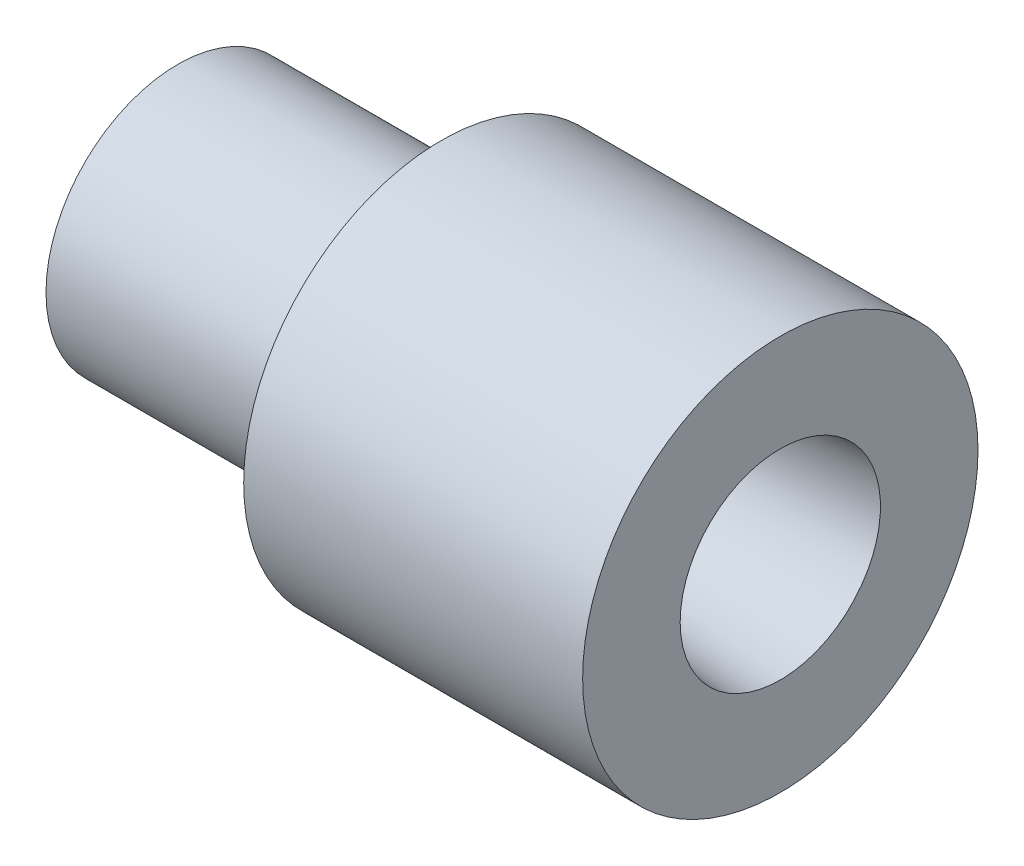
SolidWorks part; units mm, degrees
ref_plane "Front Plane" through (0, 0, 0) normal (0, 0, 1) x (1, 0, 0)
ref_plane "Top Plane" through (0, 0, 0) normal (0, 1, 0) x (1, 0, 0)
ref_plane "Right Plane" through (0, 0, 0) normal (1, 0, 0) x (0, 0, -1)
sketch "Sketch1" plane through (0, 0, 0) normal (0, 1, 0) x (1, 0, 0)
  line L0 (0, 0) -> (0, 2.286) construction
  line L1 (0, 2.286) -> (0, 6.35)
  line L2 (12.7, 9.525) -> (29.0323, 9.525)
  line L3 (29.0323, 9.525) -> (29.0323, 4.826)
  line L4 (29.0323, 4.826) -> (0, 2.286)
  line L5 (0, 0) -> (29.0323, 0) construction
  line L6 (29.0323, 0) -> (29.0323, 4.826) construction
  line L8 (12.7, 6.35) -> (12.7, 9.525)
  line L12 (0, 6.35) -> (12.7, 6.35)
  dimension "D1" = 2.286
  dimension "D2" = 4.826
  dimension "D3" = 5
  dimension "D4" = 9.525
  dimension "D5" = 6.35
  dimension "D6" = 12.7
revolve "Revolve1" add sketch "Sketch1" angle 360 about L5
equation "\"z\" = 8\t\t\t\t'number of blades"
equation "\"de\" = 0.43in\t\t\t'entrance eye diameter"
equation "\"de_length\" = 10mm\t\t'entrance eye consistent length"
equation "\"d_exit\" = 0.18in \t\t'throat aka d1"
equation "\"d2\" = 2.1in \t\t\t'outer diameter of the impeller"
equation "\"b2\" = .2in\t\t\t'tip height from disc surface at d2; slightly higher than d_exit"
equation "\"b1\" = \"b2\" + (\"d2\"/2 - \"de\"/2)*tan(\"theta\") \t\t\t'tip height from disc surface at inlet eye"
equation "\"theta\" = 12\t\t\t'angle of blades from inner to outer "
equation "\"ae\" = 3.14*(\"de\"^2)/4\t\t'entrance eye area'"
equation "\"ce\" = 3.14*\"de\"\t\t'entrance eye circumference"
equation "\"av_ratio\" = .325\t\t'ratio of av/ae at N_s of 470, range is .275 to .375, .325 ideal. High ratio means bigger area means smaller blades"
equation "\"av\" = \"ae\"*\"av_ratio\"\t\t'area between just two blades"
equation "\"s_open\" = \"av\"/\"b1\"\t\t'width of open area"
equation "\"s\"=\"ce\" - \"z\"*\"s_open\""
equation "\"min blade thickness\" = .15in"
equation "\"bearing OD\" = 30mm"
equation "\"bearing ID\"= 10mm"
equation "\"bearing depth\"= 9mm"
equation "\"bearing outer race thickness\"= 1mm"
equation "\"bearing inner race thickness\"= 1mm"
equation "\"bearing bore\" = \"bearing depth\" + 1mm"
equation "\"lower seal OD\" = .917in\t\t'this is https://www.mcmaster.com/#9281k121/=174001b"
equation "\"lower seal ID\"= .375in"
equation "\"lower seal depth\" = .625in + .218in"
equation "\"lower seal bore\" = \"lower seal depth\" + 1mm"
equation "\"upper seal OD\" = 1.125in\t'this is https://www.mcmaster.com/#5154t33/=173zuau, needs to be visually inspected before machining!"
equation "\"upper seal ID\"= 0.625in"
equation "\"upper seal depth\"= .25in\t'aka height; these values need to be confirmed by inspection!! We may want to compress the height."
equation "\"upper seal bore\" = \"upper seal depth\" + 1mm"
equation "\"big o-ring thickness\" = .139in"
equation "\"big o-ring OD\" = 2.734in"
equation "\"big o-ring ID\" = 3.012in"
equation "\"big o-ring groove depth\" = \"big o-ring thickness\"*4/5"
equation "\"impeller center height\" = \"impeller base thickness\" + \"b1\"\t'impeller height at de"
equation "\"impeller outer height\" = \"impeller base thickness\" + \"b2\"\t'impeller height at de"
equation "\"impeller upper clearance\"= .5mm"
equation "\"impeller horizontal clearance\"= (\"d2\"*1.15 - \"d2\")/2 \t\t'clearance based on D2-D3 ratio for circular volute, ranges 1.15 to 1.2"
equation "\"impeller bottom clearance\"= .5mm"
equation "\"impeller base thickness\"= 2mm"
equation "\"impeller dowel diameter\" = 2mm"
equation "\"impeller bolt head diameter\" = \"m4 head bore diameter\""
equation "\"impeller bolt head depth\" = 4mm"
equation "\"impeller bolt stop depth\" = 3mm"
equation "\"impeller bolt bore\" = \"m4 clearance\""
equation "\"impeller shaft bore depth\" = 12mm"
equation "\"impeller shaft bore\" = 8mm"
equation "\"impeller boss depth\" = \"impeller shaft bore depth\"+\"impeller bolt stop depth\"+\"impeller bolt head depth\"-\"impeller base thickness\""
equation "\"impeller boss diameter\" = \"upper seal ID\""
equation "\"impeller dowel length\" = 2mm*2 + \"impeller shaft bore\""
equation "\"coupler motor shaft hole ID\"= 8mm"
equation "\"coupler OD\"= 17mm"
equation "\"coupler length\"= 25mm"
equation "\"motor OD\" = 64mm"
equation "\"motor shaft diameter\"= 8mm"
equation "\"motor shaft pride\"= 32mm"
equation "\"motor to bearing plate distance\" = \"motor shaft pride\" + 2mm +\"coupler length\"/2"
equation "\"square plate bolt bore\" = \"m8 clearance\""
equation "\"square plate bolt head diameter\" = 13.5mm"
equation "\"square plate bolt head depth\" = 8mm"
equation "\"square plate bolt pattern diameter\"= 3.5in"
equation "\"motor mount center bore\"= \"coupler OD\"+ 4mm"
equation "\"motor mount post radius\"= ( 3 * \"square plate bolt bore\" ) / 2"
equation "\"motor mount m4 screw hole diameter\"= 4mm"
equation "\"motor mount m4 head diameter\"= 7.25mm"
equation "\"motor mount m4 head depth\"= 4mm"
equation "\"motor mount m4 pattern diamater\" = 30mm"
equation "\"motor mount plate thickness\"= 8mm + \"motor mount m4 head depth\""
equation "\"bearing plate stop ID\" = \"bearing OD\" - 4mm"
equation "\"bearing plate stop depth\" = 3mm"
equation "\"bearing plate thickness\" = \"bearing bore\" + \"bearing plate stop depth\" + \"shaft bearing stop length\""
equation "\"lower seal plate lip depth\" = 2mm"
equation "\"lower seal plate lip ID\" = \"lower seal OD\" - 3mm"
equation "\"lower seal plate thickness\" = \"lower seal plate lip depth\" + \"lower seal bore\""
equation "\"shaft coupler section diameter\" = 8mm"
equation "\"shaft coupler section length\" = \"motor to bearing plate distance\" - \"motor shaft pride\" - 2mm"
equation "\"shaft bearing section diameter\" = \"bearing ID\""
equation "\"shaft bearing section length\" = \"bearing plate stop depth\" + \"bearing depth\""
equation "\"shaft bearing stop diameter\" = \"bearing ID\" + 4mm"
equation "\"shaft bearing stop length\" = 3mm"
equation "\"shaft lower seal section diameter\" = \"lower seal ID\""
equation "\"shaft lower seal section length\" = \"lower seal plate thickness\" + 1mm"
equation "\"shaft impeller section diameter\" = \"impeller shaft bore\""
equation "\"shaft impeller section length\" = \"upper seal plate thickness\" + \"upper seal plate riser\" + \"impeller bottom clearance\" + \"impeller base thickness\" - \"impeller bolt head depth\" - \"impeller bolt stop depth\""
equation "\"upper seal plate thickness\" = \"upper seal plate pressure hole diameter\"+10mm"
equation "\"upper seal plate lip ID\" = \"upper seal OD\" - 3mm"
equation "\"upper seal plate riser\" = 6.59mm \t\t'this number needs to be read from the housing file"
equation "\"upper seal plate pressure hole diameter\" = .125in\t'this is 1/8 drill "
equation "\"upper seal plate pressure tap diameter\" = .328125in \t'this is 21/64 drill for a 1/8 ANPT tap"
equation "\"upper seal plate pressure tap grip\" = 5mm\t\t'this is the area around the tap so it doesn't crack"
equation "\"upper seal plate pressure tap depth\" = 12mm"
equation "\"impeller cavity center height\"= \"impeller bottom clearance\" + \"impeller upper clearance\" + \"impeller center height\""
equation "\"impeller cavity diameter\"= 2 * \"impeller horizontal clearance\" + \"d2\" \t\t\t\t\t\t\t\t\t'called D3 analytically"
equation "\"impeller cavity outer height\"= \"impeller bottom clearance\" + \"impeller upper clearance\" + \"impeller base thickness\" + \"b2\" \t\t'this is height at impeller diameter d2, not at d3"
equation "\"impeller housing thickness\"= \"impeller housing exit threaded diameter\" + 2*\"impeller housing outlet grip\""
equation "\"impeller housing diameter\" = \"square plate bolt pattern diameter\" + 2*\"motor mount post radius\""
equation "\"impeller housing bolt count\" = 6"
equation "\"impeller housing bolt diameter\" = \"m6 clearance\""
equation "\"impeller housing bolt pattern diameter\" = 3.5in"
equation "\"impeller housing threaded inlet diameter\" = 0.515625in \t'this is the 33/64 drill size for 9/16-18 fitting, expecting swagelok SS-8FK0-1-6STH fitting"
equation "\"impeller housing threaded inlet depth\"= 10mm"
equation "\"impeller housing exit threaded diameter\"= 0.515625in \t\t'this is the 33/64 drill size for 9/16-18 fitting, expecting swagelok SS-8FK0-1-6STH fitting"
equation "\"impeller housing exit threaded depth\"= 10mm"
equation "\"impeller housing diffuser conical angle\"=10"
equation "\"impeller housing diffuser tangent angle\"=5"
equation "\"impeller housing diffuser final diameter\" = .38in\t\t'aka d2'"
equation "\"impeller housing outlet grip\" = 5mm"
equation "\"end mill size\" = 0.375in\t'for 3/8 endmill"
equation "\"m4 clearance\" = 0.171875in \t'this is 11/64 bit for 4.36mm"
equation "\"m4 tap\" = 0.125in\t\t'this is 1/8 bit for 3.17mm"
equation "\"m4 head bore diameter\" = 7.5mm"
equation "\"m4 head bore depth\" = 5mm\t'actual is ~4mm"
equation "\"m6 clearance\" = 0.234375in\t'this is 15/64 bit = 5.95mm, could use 6mm bit, B bit for 6.04mm or 1/4 bit for 6.35mm"
equation "\"m6 tap\" = 5mm\t\t\t'5mm is appropriate, could use 13/64 or #5,6,7"
equation "\"m6 head bore diameter\" = 11mm\t\t"
equation "\"m6 head bore depth\" = 7mm\t'actual is 6mm"
equation "\"m8 clearance\" = 0.3125in\t'this is 5/16in for 7.93mm, could use 8mm, O,P, or 21/64"
equation "\"m8 tap\" = 0.265625in\t\t'this is 17/64 for 6.746875mm"
equation "\"m8 head bore diameter\" = 14mm"
equation "\"m8 head bore depth\" = 9mm\t'actual is 8mm"
equation "\"D1@Sketch1\"=\"d_exit\"/2"
equation "\"D2@Sketch1\"=\"impeller housing diffuser final diameter\"/2"
equation "\"diffuser cartridge OD\" =.75in"
equation "\"D4@Sketch1\"=\"diffuser cartridge OD\"/2"
